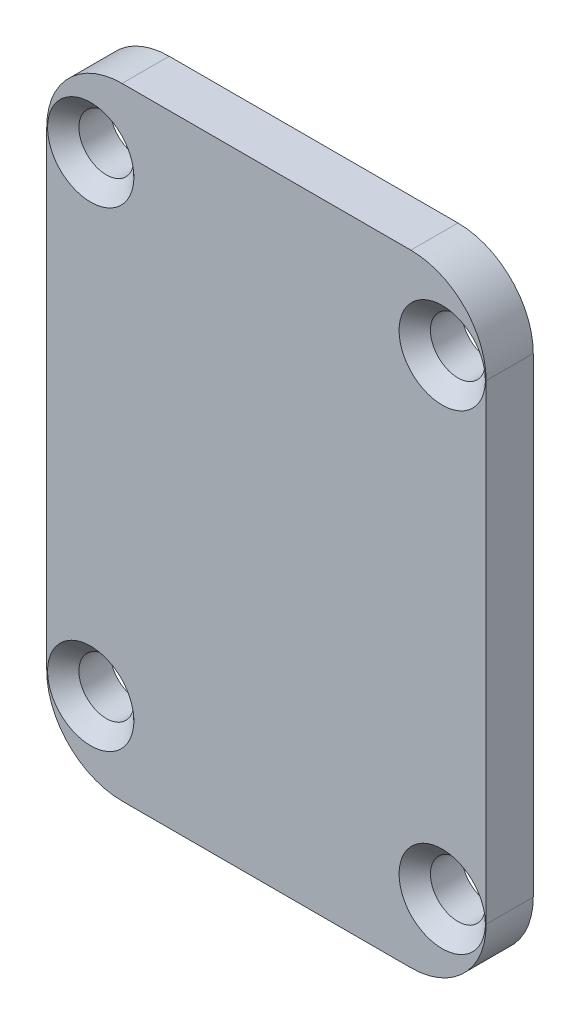
SolidWorks part; units mm, degrees
ref_plane "Płaszczyzna przednia" through (0, 0, 0) normal (0, 0, 1) x (1, 0, 0)
ref_plane "Płaszczyzna górna" through (0, 0, 0) normal (0, 1, 0) x (1, 0, 0)
ref_plane "Płaszczyzna prawa" through (0, 0, 0) normal (1, 0, 0) x (0, 0, -1)
sketch "Szkic1" plane through (0, 0, 0) normal (0, 0, 1) x (1, 0, 0)
  line L1 (-14.2, -20) -> (14.2, -20)
  line L2 (-14.2, -20) -> (-14.2, 20)
  line L3 (-14.2, 20) -> (14.2, 20)
  line L4 (14.2, -20) -> (14.2, 20)
  line L5 (-14.2, -20) -> (14.2, 20) construction
  line L6 (-14.2, 20) -> (14.2, -20) construction
  point P0 (0, 0)
  dimension "D1" = 40
  dimension "D2" = 28.4
extrude "Dodanie-wyciągnięcie1" add sketch "Szkic1" along normal blind 3
fillet "Zaokrąglenie1" radius 5 4 edges at (-14.2, -20, 1.5) (14.2, -20, 1.5) (-14.2, 20, 1.5) (14.2, 20, 1.5)
sketch "Szkic2" plane through (0, 0, 3) normal (0, 0, 1) x (1, 0, 0)
  line L0 (0, -20) -> (0, 20) construction
  line L1 (-9.2, -20) -> (9.2, -20) construction
  line L2 (9.2, 20) -> (-9.2, 20) construction
  circle A0 centre (-11.2, 15) radius 1.75
  circle A1 centre (11.2, 15) radius 1.75
  circle A2 centre (-11.2, -15) radius 1.75
  circle A3 centre (11.2, -15) radius 1.75
  point P8 (0, 0)
  point P9 (0, 0)
  point P16 (0, 0)
  dimension "D1" = 3.5
  dimension "D2" = 22.4
  dimension "D3" = 30
  dimension "D4" = 5
extrude "Wytnij-wyciągnięcie1" cut sketch "Szkic2" against normal blind 3
chamfer "Sfazowanie1" distance 1 angle 45 4 edges at (-9.45, -15, 3) (12.95, -15, 3) (-9.45, 15, 3) (12.95, 15, 3)
sketch "Szkic3" plane through (0, 0, 3) normal (0, 0, 1) x (1, 0, 0)
  line L0 (9.2, 19.8) -> (-9.2, 19.8)
  line L1 (-14, 15) -> (-14, -15)
  line L2 (-9.2, -19.8) -> (9.2, -19.8)
  line L3 (14, -15) -> (14, 15)
  line L4 (-14.2, 15) -> (-14.2, -15)
  line L5 (-9.2, -20) -> (9.2, -20)
  line L6 (14.2, -15) -> (14.2, 15)
  line L7 (9.2, 20) -> (-9.2, 20)
  line L8 (-14.2, 15) -> (-14.2, -15)
  line L9 (-9.2, -20) -> (9.2, -20)
  line L10 (14.2, -15) -> (14.2, 15)
  line L11 (9.2, 20) -> (-9.2, 20)
  arc A0 (-9.2, 19.8) -> (-14, 15) centre (-9.2, 15) ccw
  arc A1 (-14, -15) -> (-9.2, -19.8) centre (-9.2, -15) ccw
  arc A2 (9.2, -19.8) -> (14, -15) centre (9.2, -15) ccw
  arc A3 (14, 15) -> (9.2, 19.8) centre (9.2, 15) ccw
  arc A4 (-14.2, -15) -> (-9.2, -20) centre (-9.2, -15) ccw
  arc A5 (9.2, -20) -> (14.2, -15) centre (9.2, -15) ccw
  arc A6 (14.2, 15) -> (9.2, 20) centre (9.2, 15) ccw
  arc A7 (-9.2, 20) -> (-14.2, 15) centre (-9.2, 15) ccw
  arc A8 (-14.2, -15) -> (-9.2, -20) centre (-9.2, -15) ccw
  arc A9 (9.2, -20) -> (14.2, -15) centre (9.2, -15) ccw
  arc A10 (14.2, 15) -> (9.2, 20) centre (9.2, 15) ccw
  arc A11 (-9.2, 20) -> (-14.2, 15) centre (-9.2, 15) ccw
  dimension "D1" = 0
  dimension "D2" = 0.2
extrude "Wytnij-wyciągnięcie2" cut sketch "Szkic3" against normal blind 3
